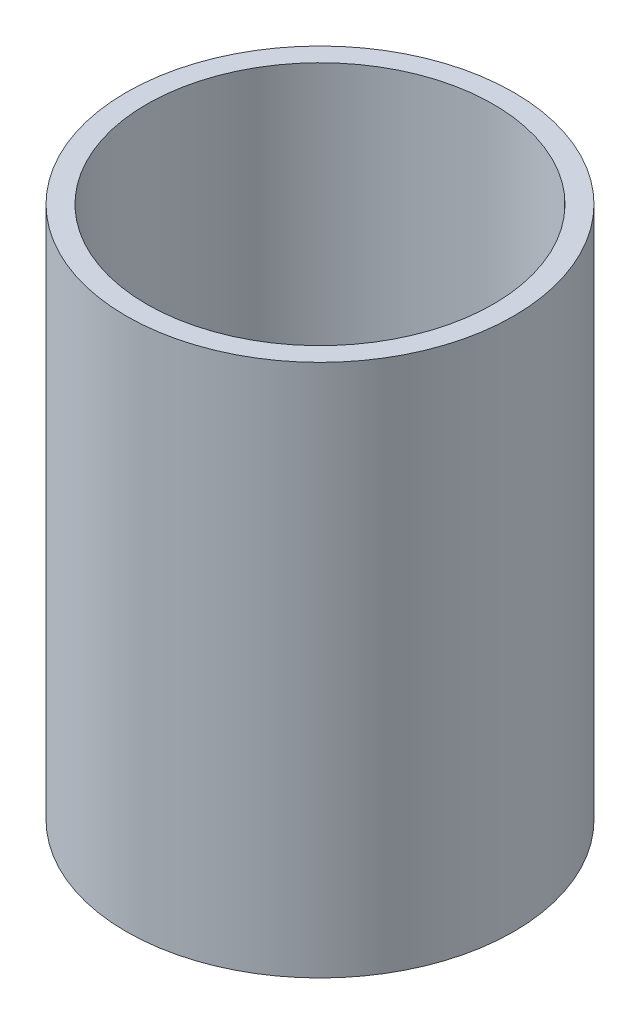
SolidWorks part; units mm, degrees
ref_plane "Front Plane" through (0, 0, 0) normal (0, 0, 1) x (1, 0, 0)
ref_plane "Top Plane" through (0, 0, 0) normal (0, 1, 0) x (1, 0, 0)
ref_plane "Right Plane" through (0, 0, 0) normal (1, 0, 0) x (0, 0, -1)
sketch "Sketch1" plane through (0, 0, 0) normal (0, 1, 0) x (1, 0, 0)
  circle A0 centre (0, 0) radius 15.99
  circle A1 centre (0, 0) radius 14.3
  dimension "D1" = 31.98
  dimension "D2" = 28.6
extrude "Boss-Extrude1" add sketch "Sketch1" along normal blind 44
